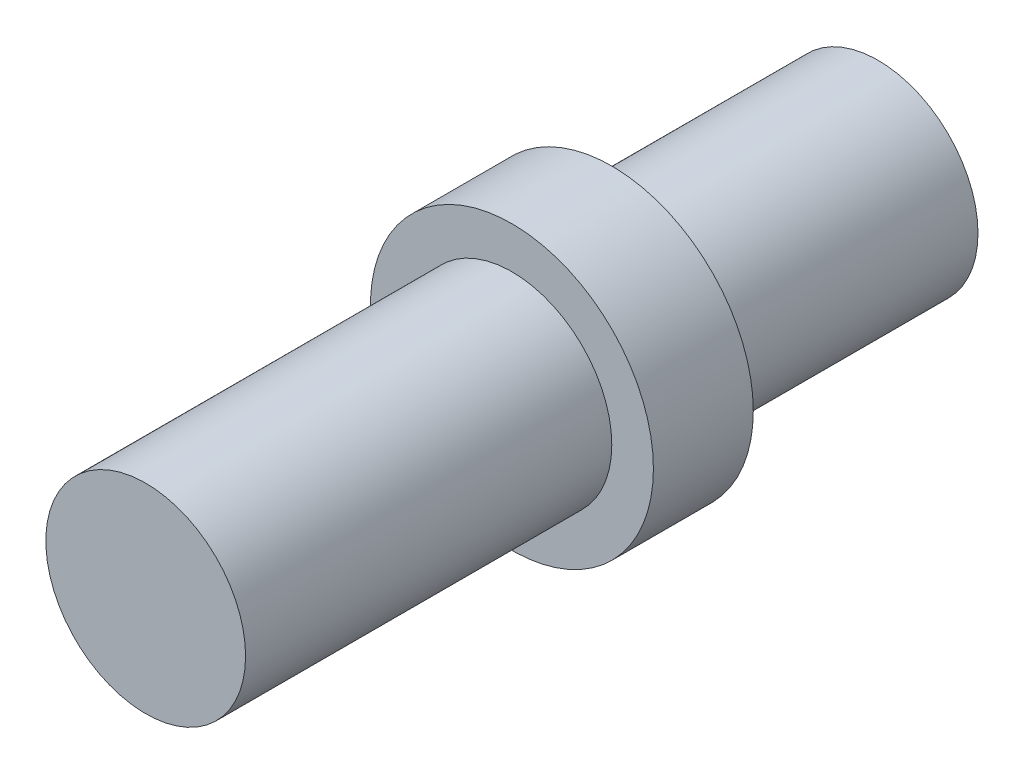
SolidWorks part; units mm, degrees
ref_plane "前视基准面" through (0, 0, 0) normal (0, 0, 1) x (1, 0, 0)
ref_plane "上视基准面" through (0, 0, 0) normal (0, 1, 0) x (1, 0, 0)
ref_plane "右视基准面" through (0, 0, 0) normal (1, 0, 0) x (0, 0, -1)
other "Configuration Table"
sketch "草图1" plane through (0, 0, 0) normal (0, 0, 1) x (1, 0, 0)
  circle A0 centre (0, 0) radius 6
extrude "凸台-拉伸1" add sketch "草图1" along normal blind 44
sketch "草图2" plane through (0, 0, 0) normal (0, 0, 1) x (1, 0, 0)
  circle A0 centre (0, 0) radius 8.5
extrude "凸台-拉伸2" add sketch "草图2" along normal blind 6 from offset 16
